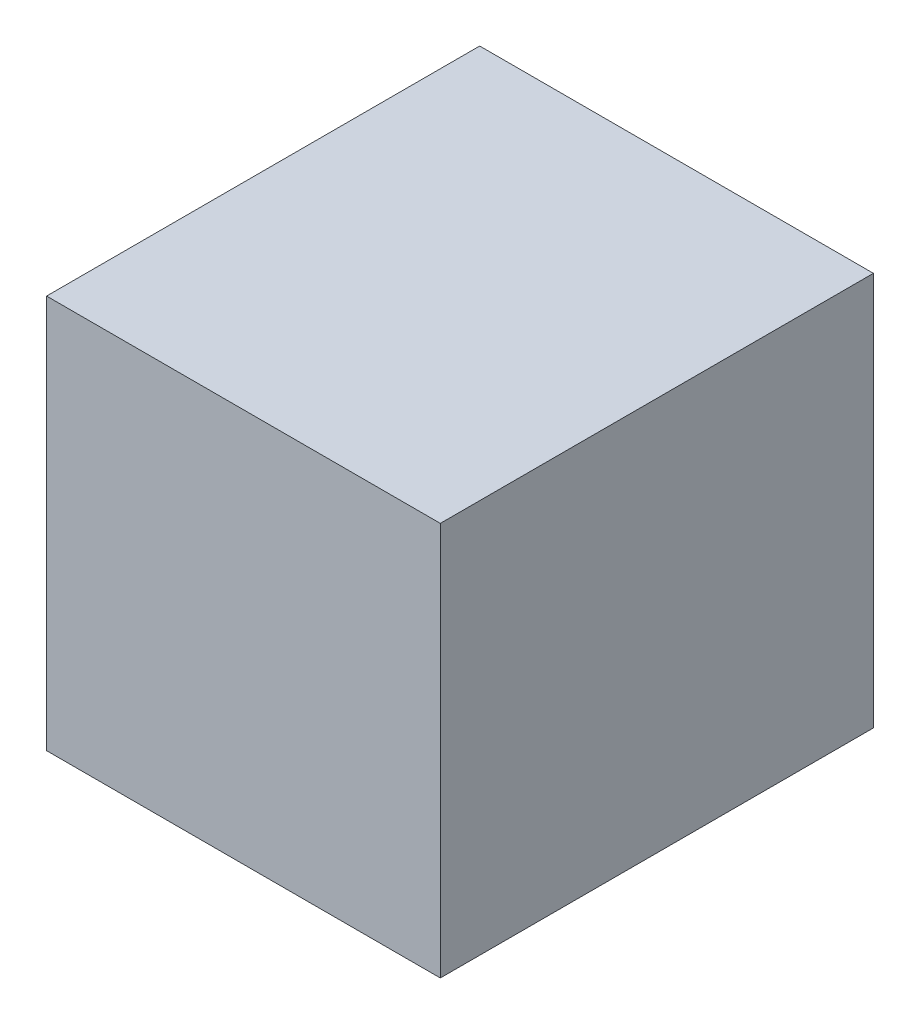
SolidWorks part; units mm, degrees
ref_plane "Front Plane" through (0, 0, 0) normal (0, 0, 1) x (1, 0, 0)
ref_plane "Top Plane" through (0, 0, 0) normal (0, 1, 0) x (1, 0, 0)
ref_plane "Right Plane" through (0, 0, 0) normal (1, 0, 0) x (0, 0, -1)
other "Configuration Table"
sketch "Sketch1" plane through (0, 0, 0) normal (0, 0, 1) x (1, 0, 0)
  line L1 (200, 180) -> (300, 180)
  line L2 (200, 180) -> (200, 280)
  line L3 (200, 280) -> (300, 280)
  line L4 (300, 180) -> (300, 280)
extrude "PACK_pano_psu_24V_1" add sketch "Sketch1" against normal blind 110 from offset 138 separate body
